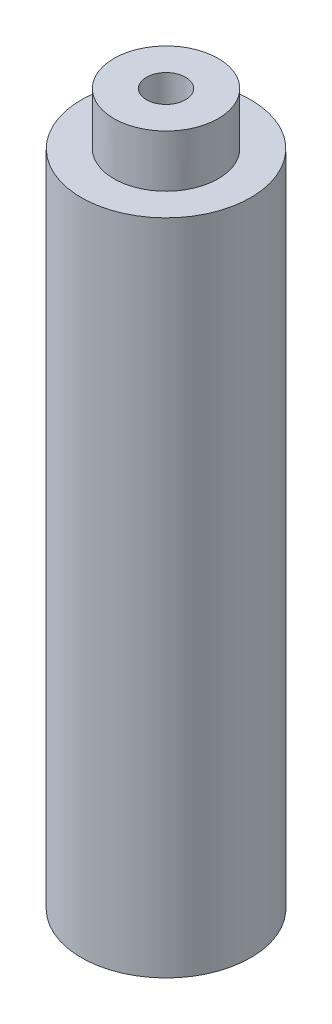
SolidWorks part; units mm, degrees
ref_plane "Front Plane" through (0, 0, 0) normal (0, 0, 1) x (1, 0, 0)
ref_plane "Top Plane" through (0, 0, 0) normal (0, 1, 0) x (1, 0, 0)
ref_plane "Right Plane" through (0, 0, 0) normal (1, 0, 0) x (0, 0, -1)
sketch "Sketch1" plane through (0, 0, 0) normal (0, 1, 0) x (1, 0, 0)
  circle A0 centre (0, 0) radius 0.75
  circle A1 centre (0, 0) radius 2
  dimension "D1" = 1.5
  dimension "D2" = 4
extrude "Boss-Extrude1" add sketch "Sketch1" along normal blind 2
sketch "Sketch2" plane through (0, 0, 0) normal (0, -1, 0) x (1, 0, 0)
  circle A0 centre (0, 0) radius 3.25
  circle A1 centre (0, 0) radius 0.75 construction
  circle A2 centre (0, 0) radius 0.75
  dimension "D1" = 6.5
extrude "Boss-Extrude2" add sketch "Sketch2" along normal blind 0.25
sketch "Sketch3" plane through (0, -0.25, 0) normal (0, -1, 0) x (1, 0, 0)
  circle A0 centre (0, 0) radius 3
  circle A1 centre (0, 0) radius 3.25
  circle A2 centre (0, 0) radius 3.25
  dimension "D1" = 0
  dimension "D2" = 0.25
extrude "Boss-Extrude3" add sketch "Sketch3" along normal blind 25
